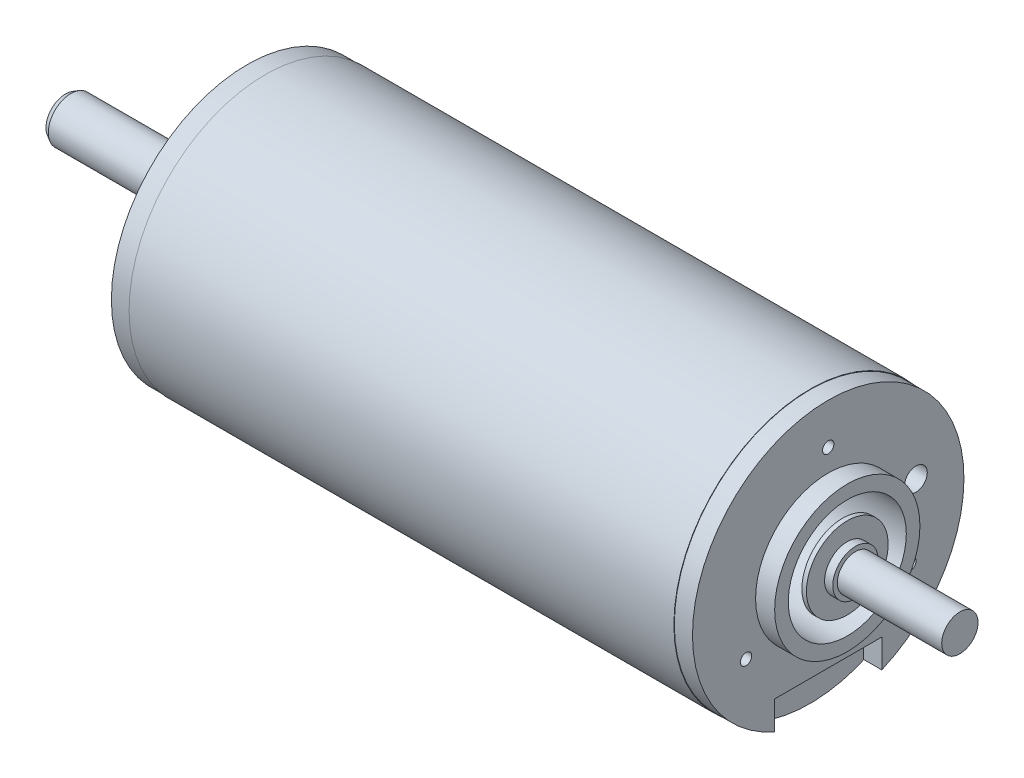
SolidWorks part; units mm, degrees
ref_plane "Front Plane" through (0, 0, 0) normal (0, 0, 1) x (1, 0, 0)
ref_plane "Top Plane" through (0, 0, 0) normal (0, 1, 0) x (1, 0, 0)
ref_plane "Right Plane" through (0, 0, 0) normal (1, 0, 0) x (0, 0, -1)
ref_plane "Plane1" through (0, 0, 0) normal (0, 0, -1) x (-1, 0, 0)
sketch "Sketch1" plane through (0, 0, 0) normal (0, 0, -1) x (-1, 0, 0)
  line L0 (-62, 15) -> (-62, 0)
  line L1 (-62, 0) -> (-2, 0)
  line L2 (-2, 0) -> (-2, 15)
  line L3 (-2, 15) -> (-62, 15)
  line L4 (-62, 0) -> (-2, 0) construction
revolve "Revolve1" add sketch "Sketch1" angle 360 about L4
sketch "Sketch2" plane through (62, 0, 0) normal (1, 0, 0) x (0, 0, -1)
  line L0 (5.9, -13.7365) -> (5.9, -10.6)
  line L1 (5.9, -10.6) -> (-5.9, -10.6)
  line L2 (-5.9, -10.6) -> (-5.9, -13.7365)
  arc A0 (-5.9, -13.7365) -> (5.9, -13.7365) centre (0, 0) cw
extrude "Boss-Extrude1" add sketch "Sketch2" along normal blind 2
sketch "Sketch3" plane through (64, 0, 0) normal (1, 0, 0) x (0, 0, -1)
  circle A0 centre (0, 0) radius 8
extrude "Boss-Extrude2" add sketch "Sketch3" along normal blind 2.1
hole_wizard "Hole1" positions "Sketch5" profile "Sketch4" legacy
sketch "Sketch5" plane through (66.1, 0, 0) normal (1, 0, 0) x (0, 0, -1)
  point P0 (0, 0)
sketch "Sketch4" plane through (66.1, 0, 0) normal (0, 1, 0) x (0, 0, -1)
  line L0 (0, 0) -> (0, 0.5)
  line L1 (0, 0.5) -> (6.5, 0.5)
  line L2 (6.5, 0.5) -> (6.5, 0)
  line L3 (6.5, 0) -> (0, 0)
  line L4 (0, 110) -> (0, -10) construction
  dimension "Diameter" = 13
  dimension "Depth" = 0.5
sketch "Sketch6" plane through (2, 0, 0) normal (-1, 0, 0) x (0, 0, 1)
  circle A0 centre (0, 0) radius 14.95
extrude "Boss-Extrude3" add sketch "Sketch6" along normal blind 2
sketch "Sketch7" plane through (0, 0, 0) normal (-1, 0, 0) x (0, 0, 1)
  circle A0 centre (0, 0) radius 8
extrude "Boss-Extrude4" add sketch "Sketch7" along normal blind 1.2
hole_wizard "Hole2" positions "Sketch9" profile "Sketch8" legacy
sketch "Sketch9" plane through (-1.2, 0, 0) normal (-1, 0, 0) x (0, 0, 1)
  point P0 (0, 0)
sketch "Sketch8" plane through (-1.2, 0, 0) normal (0, 1, 0) x (0, 0, 1)
  line L0 (0, 0) -> (0, 67.3)
  line L1 (0, 67.3) -> (6.5, 67.3)
  line L2 (6.5, 67.3) -> (6.5, 0)
  line L3 (6.5, 0) -> (0, 0)
  line L4 (0, 110) -> (0, -10) construction
  dimension "Diameter" = 13
  dimension "Depth" = 67.3
sketch "Sketch10" plane through (0, 0, 0) normal (0, 0, -1) x (-1, 0, 0)
  line L0 (0.7, 4.5) -> (0.7, 0)
  line L1 (0.7, 0) -> (20, 0)
  line L2 (20, 0) -> (20, 2.5)
  line L3 (20, 2.5) -> (1.2, 2.5)
  line L4 (1.2, 2.5) -> (1.2, 4.5)
  line L5 (1.2, 4.5) -> (0.7, 4.5)
  line L6 (0.7, 0) -> (20, 0) construction
revolve "Revolve2" add sketch "Sketch10" angle 360 about L6
sketch "Sketch11" plane through (0, 0, 0) normal (0, 0, -1) x (-1, 0, 0)
  line L0 (-78.5, 2) -> (-78.5, 0)
  line L1 (-78.5, 0) -> (-65.6, 0)
  line L2 (-65.6, 0) -> (-65.6, 4.5)
  line L3 (-65.6, 4.5) -> (-66.1, 4.5)
  line L4 (-66.1, 4.5) -> (-66.1, 2.5)
  line L5 (-66.1, 2.5) -> (-67, 2.5)
  line L6 (-67, 2.5) -> (-67, 2)
  line L7 (-67, 2) -> (-78.5, 2)
  line L8 (-78.5, 0) -> (-65.6, 0) construction
revolve "Revolve3" add sketch "Sketch11" angle 360 about L8
hole_wizard "Hole3" positions "Sketch13" profile "Sketch12" legacy
sketch "Sketch13" plane through (0, 0, 0) normal (-1, 0, 0) x (0, 0, 1)
  point P0 (8.6603, -5)
sketch "Sketch12" plane through (0, -5, 8.6603) normal (0, 1, 0) x (0, 0, 1)
  line L0 (0, 0) -> (0, 2)
  line L1 (0, 2) -> (1.25, 2)
  line L2 (1.25, 2) -> (1.25, 0)
  line L3 (1.25, 0) -> (0, 0)
  line L4 (0, 110) -> (0, -10) construction
  dimension "Diameter" = 2.5
  dimension "Depth" = 2
hole_wizard "Hole4" positions "Sketch15" profile "Sketch14" legacy
sketch "Sketch15" plane through (64, 0, 0) normal (1, 0, 0) x (0, 0, -1)
  point P0 (9.6593, 2.5882)
sketch "Sketch14" plane through (64, 2.5882, -9.6593) normal (0, 1, 0) x (0, 0, -1)
  line L0 (0, 0) -> (0, 2)
  line L1 (0, 2) -> (1.25, 2)
  line L2 (1.25, 2) -> (1.25, 0)
  line L3 (1.25, 0) -> (0, 0)
  line L4 (0, 110) -> (0, -10) construction
  dimension "Diameter" = 2.5
  dimension "Depth" = 2
hole_wizard "Hole5" positions "Sketch17" profile "Sketch16" legacy
sketch "Sketch17" plane through (0, 0, 0) normal (-1, 0, 0) x (0, 0, 1)
  point P0 (11, 0)
sketch "Sketch16" plane through (0, 0, 11) normal (0, 1, 0) x (0, 0, 1)
  line L0 (0, 0) -> (0, 7.2511)
  line L1 (0, 7.2511) -> (1.25, 6.5)
  line L2 (1.25, 6.5) -> (1.25, 0)
  line L4 (1.25, 0) -> (0, 0)
  line L6 (0, 7.2511) -> (-1.25, 6.5) construction
  line L7 (0, -4.2442) -> (0, 117.3081) construction
  dimension "Diameter" = 2.5
  dimension "Depth" = 6.5
  dimension "Drill Angle" = 118
hole_wizard "Hole6" positions "Sketch19" profile "Sketch18" legacy
sketch "Sketch19" plane through (0, 0, 0) normal (-1, 0, 0) x (0, 0, 1)
  point P0 (0, 11)
sketch "Sketch18" plane through (0, 11, 0) normal (0, 1, 0) x (0, 0, 1)
  line L0 (0, 0) -> (0, 7.2511)
  line L1 (0, 7.2511) -> (1.25, 6.5)
  line L2 (1.25, 6.5) -> (1.25, 0)
  line L4 (1.25, 0) -> (0, 0)
  line L6 (0, 7.2511) -> (-1.25, 6.5) construction
  line L7 (0, -4.2442) -> (0, 117.3081) construction
  dimension "Diameter" = 2.5
  dimension "Depth" = 6.5
  dimension "Drill Angle" = 118
hole_wizard "Hole7" positions "Sketch21" profile "Sketch20" legacy
sketch "Sketch21" plane through (0, 0, 0) normal (-1, 0, 0) x (0, 0, 1)
  point P0 (-11, 0)
sketch "Sketch20" plane through (0, 0, -11) normal (0, 1, 0) x (0, 0, 1)
  line L0 (0, 0) -> (0, 7.2511)
  line L1 (0, 7.2511) -> (1.25, 6.5)
  line L2 (1.25, 6.5) -> (1.25, 0)
  line L4 (1.25, 0) -> (0, 0)
  line L6 (0, 7.2511) -> (-1.25, 6.5) construction
  line L7 (0, -4.2442) -> (0, 117.3081) construction
  dimension "Diameter" = 2.5
  dimension "Depth" = 6.5
  dimension "Drill Angle" = 118
hole_wizard "Hole8" positions "Sketch23" profile "Sketch22" legacy
sketch "Sketch23" plane through (0, 0, 0) normal (-1, 0, 0) x (0, 0, 1)
  point P0 (0, -11)
sketch "Sketch22" plane through (0, -11, 0) normal (0, 1, 0) x (0, 0, 1)
  line L0 (0, 0) -> (0, 7.2511)
  line L1 (0, 7.2511) -> (1.25, 6.5)
  line L2 (1.25, 6.5) -> (1.25, 0)
  line L4 (1.25, 0) -> (0, 0)
  line L6 (0, 7.2511) -> (-1.25, 6.5) construction
  line L7 (0, -4.2442) -> (0, 117.3081) construction
  dimension "Diameter" = 2.5
  dimension "Depth" = 6.5
  dimension "Drill Angle" = 118
hole_wizard "Hole9" positions "Sketch25" profile "Sketch24" legacy
sketch "Sketch25" plane through (64, 0, 0) normal (1, 0, 0) x (0, 0, -1)
  point P0 (0, 10.45)
sketch "Sketch24" plane through (64, 10.45, 0) normal (0, 1, 0) x (0, 0, -1)
  line L0 (0, 0) -> (0, 3.1755)
  line L1 (0, 3.1755) -> (0.625, 2.8)
  line L2 (0.625, 2.8) -> (0.625, 0)
  line L4 (0.625, 0) -> (0, 0)
  line L6 (0, 3.1755) -> (-0.625, 2.8) construction
  line L7 (0, -4.2442) -> (0, 117.3081) construction
  dimension "Diameter" = 1.25
  dimension "Depth" = 2.8
  dimension "Drill Angle" = 118
hole_wizard "Hole10" positions "Sketch27" profile "Sketch26" legacy
sketch "Sketch27" plane through (64, 0, 0) normal (1, 0, 0) x (0, 0, -1)
  point P0 (9.05, -5.225)
sketch "Sketch26" plane through (64, -5.225, -9.05) normal (0, 1, 0) x (0, 0, -1)
  line L0 (0, 0) -> (0, 3.1755)
  line L1 (0, 3.1755) -> (0.625, 2.8)
  line L2 (0.625, 2.8) -> (0.625, 0)
  line L4 (0.625, 0) -> (0, 0)
  line L6 (0, 3.1755) -> (-0.625, 2.8) construction
  line L7 (0, -4.2442) -> (0, 117.3081) construction
  dimension "Diameter" = 1.25
  dimension "Depth" = 2.8
  dimension "Drill Angle" = 118
hole_wizard "Hole11" positions "Sketch29" profile "Sketch28" legacy
sketch "Sketch29" plane through (64, 0, 0) normal (1, 0, 0) x (0, 0, -1)
  point P0 (-9.05, -5.225)
sketch "Sketch28" plane through (64, -5.225, 9.05) normal (0, 1, 0) x (0, 0, -1)
  line L0 (0, 0) -> (0, 3.1755)
  line L1 (0, 3.1755) -> (0.625, 2.8)
  line L2 (0.625, 2.8) -> (0.625, 0)
  line L4 (0.625, 0) -> (0, 0)
  line L6 (0, 3.1755) -> (-0.625, 2.8) construction
  line L7 (0, -4.2442) -> (0, 117.3081) construction
  dimension "Diameter" = 1.25
  dimension "Depth" = 2.8
  dimension "Drill Angle" = 118
chamfer "Chamfer1" distance 0.3464 angle 60 1 edges at (-20, 0, 2.5)
